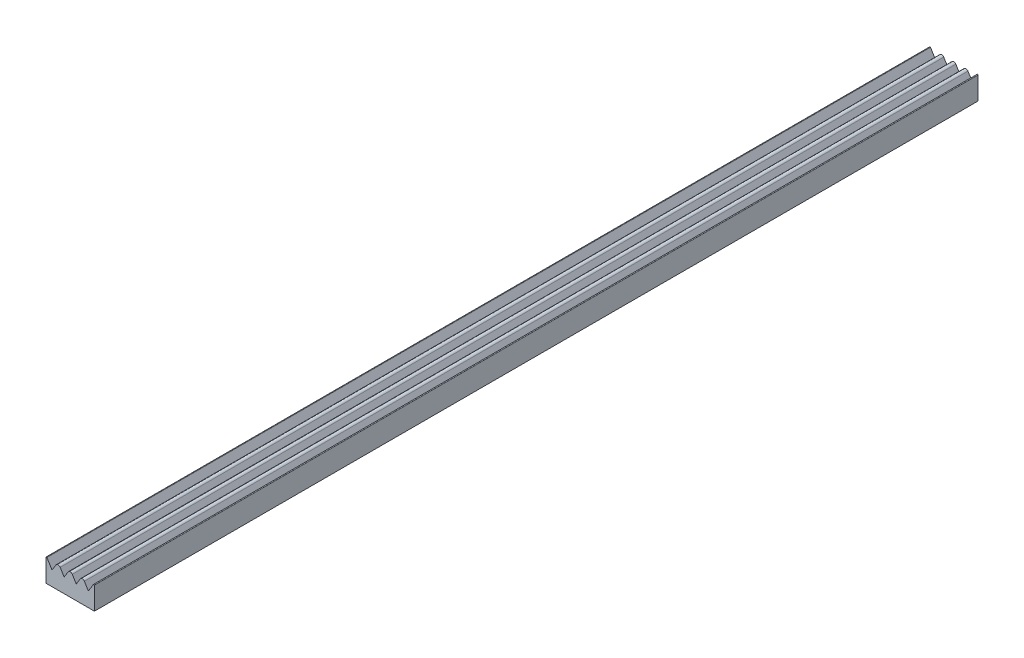
SolidWorks part; units mm, degrees
material "Polyurethane Foam Flexible"
ref_plane "Front Plane" through (0, 0, 0) normal (0, 0, 1) x (1, 0, 0)
ref_plane "Top Plane" through (0, 0, 0) normal (0, 1, 0) x (1, 0, 0)
ref_plane "Right Plane" through (0, 0, 0) normal (1, 0, 0) x (0, 0, -1)
sketch "Sketch1" plane through (0, 0, 0) normal (0, 0, 1) x (1, 0, 0)
  line L0 (-12.7, 6.35) -> (0, 6.35) construction
  line L1 (0, 0) -> (-12.7, 0)
  line L2 (0, 0) -> (0, 5.9072)
  line L3 (-6.35, 0) -> (-6.35, 6.35) construction
  line L4 (-12.7, 0) -> (-12.7, 5.9072)
  line L5 (-12.7, 3.81) -> (0, 3.81) construction
  line L6 (-7.9375, 3.81) -> (-6.8885, 5.4884)
  line L7 (-7.9375, 3.81) -> (-8.9865, 5.4884)
  line L8 (-10.0635, 5.4884) -> (-11.1125, 3.81)
  line L9 (-11.1125, 3.81) -> (-12.4653, 5.9745)
  line L10 (-4.7625, 3.81) -> (-5.8115, 5.4884)
  line L11 (-4.7625, 3.81) -> (-3.7135, 5.4884)
  line L14 (-2.6365, 5.4884) -> (-1.5875, 3.81)
  line L15 (-1.5875, 3.81) -> (-0.2347, 5.9745)
  arc A0 (-3.7135, 5.4884) -> (-2.6365, 5.4884) centre (-3.175, 5.1519) cw
  arc A1 (-6.8885, 5.4884) -> (-5.8115, 5.4884) centre (-6.35, 5.1519) cw
  arc A2 (-8.9865, 5.4884) -> (-10.0635, 5.4884) centre (-9.525, 5.1519) ccw
  arc A3 (0, 5.9072) -> (-0.2347, 5.9745) centre (-0.127, 5.9072) ccw
  arc A4 (-12.4653, 5.9745) -> (-12.7, 5.9072) centre (-12.573, 5.9072) ccw
  dimension "D7" = 0.635
  dimension "D8" = 0.127
  dimension "D1" = 6.35
  dimension "D2" = 12.7
  dimension "D3" = 1.5875
  dimension "D4" = 2.54
  dimension "D5" = 1.5875
extrude "Boss-Extrude1" add sketch "Sketch1" along normal blind 231.775
